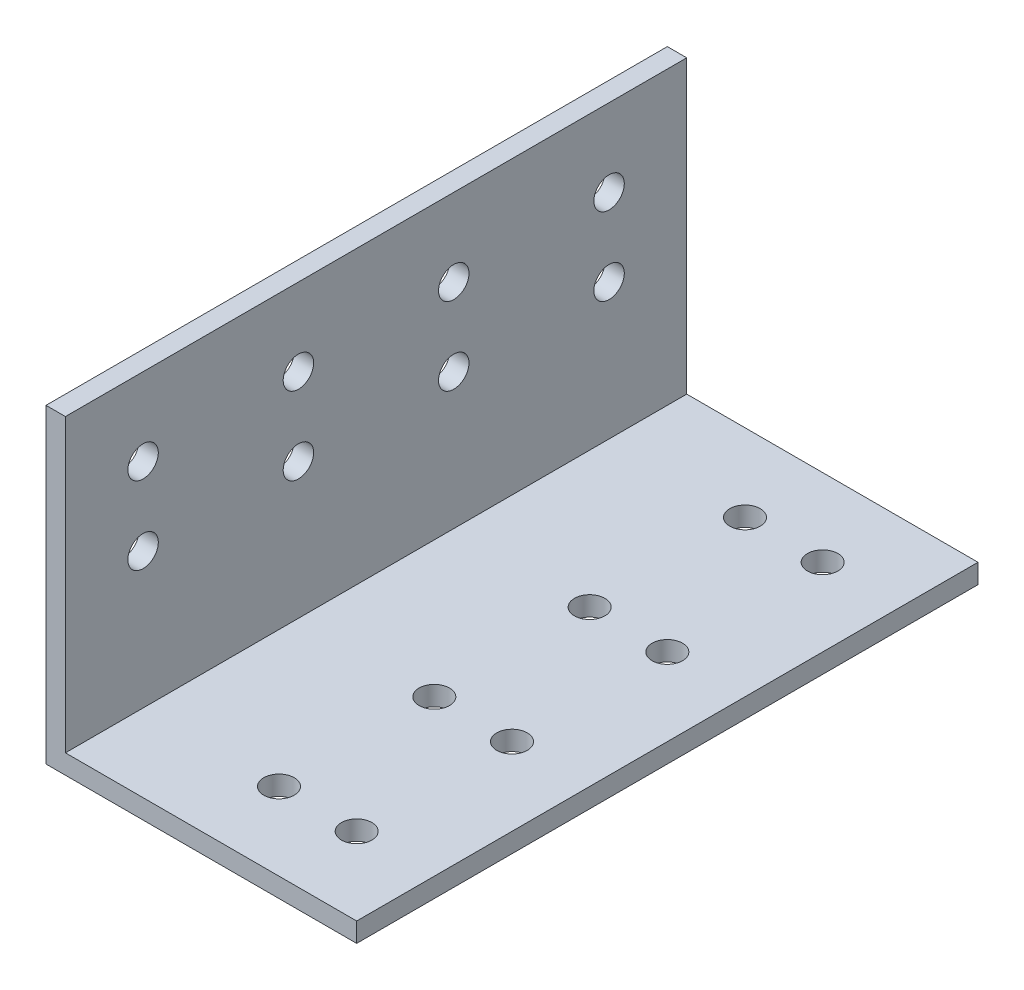
SolidWorks part; units mm, degrees
material "6061-T6 (SS)"
ref_plane "Front Plane" through (0, 0, 0) normal (0, 0, 1) x (1, 0, 0)
ref_plane "Top Plane" through (0, 0, 0) normal (0, 1, 0) x (1, 0, 0)
ref_plane "Right Plane" through (0, 0, 0) normal (1, 0, 0) x (0, 0, -1)
sketch "Sketch2" plane through (0, 0, 0) normal (0, 0, 1) x (1, 0, 0)
  line L0 (0, 0) -> (0, 50.8)
  line L1 (0, 50.8) -> (3.175, 50.8)
  line L2 (3.175, 50.8) -> (3.175, 3.175)
  line L3 (3.175, 3.175) -> (50.8, 3.175)
  line L4 (50.8, 3.175) -> (50.8, 0)
  line L5 (50.8, 0) -> (0, 0)
  dimension "D1" = 3.175
  dimension "D2" = 50.8
  dimension "D3" = 50.8
extrude "Boss-Extrude1" add sketch "Sketch2" along normal blind 101.6 contours L2 L3 L4 L5 L0 L1
sketch "Sketch3" plane through (0, 3.175, 0) normal (0, 1, 0) x (1, 0, 0)
  line L0 (3.175, -101.6) -> (3.175, 0) construction
  line L1 (3.175, 0) -> (50.8, 0) construction
  circle A0 centre (25.4, -12.7) radius 2.4892
  circle A1 centre (38.1, -12.7) radius 2.4892
  circle A2 centre (38.1, -38.1) radius 2.4892
  circle A3 centre (38.1, -63.5) radius 2.4892
  circle A4 centre (38.1, -88.9) radius 2.4892
  circle A5 centre (25.4, -38.1) radius 2.4892
  circle A6 centre (25.4, -63.5) radius 2.4892
  circle A7 centre (25.4, -88.9) radius 2.4892
  point P20 (0, 0)
  dimension "D3" = 12.7
  dimension "D4" = 25.4
  dimension "D5" = 22.225
  dimension "D6" = 4.9784
  dimension "D7" = 12.7
  dimension "D1" = 2
  dimension "D2" = 4
extrude "Cut-Extrude1" cut sketch "Sketch3" against normal through all
sketch "Sketch4" plane through (3.175, 0, 0) normal (1, 0, 0) x (0, 0, -1)
  line L0 (0, 50.8) -> (0, 3.175) construction
  line L1 (-101.6, 3.175) -> (0, 3.175) construction
  circle A0 centre (-12.7, 25.4) radius 2.4892
  circle A1 centre (-38.1, 25.4) radius 2.4892
  circle A2 centre (-63.5, 25.4) radius 2.4892
  circle A3 centre (-88.9, 25.4) radius 2.4892
  circle A4 centre (-38.1, 38.1) radius 2.4892
  circle A5 centre (-63.5, 38.1) radius 2.4892
  circle A6 centre (-88.9, 38.1) radius 2.4892
  circle A7 centre (-12.7, 38.1) radius 2.4892
  point P20 (0, 0)
  point P21 (0, 0)
  dimension "D3" = 12.7
  dimension "D4" = 12.7
  dimension "D5" = 25.4
  dimension "D6" = 22.225
  dimension "D7" = 4.9784
  dimension "D1" = 4
  dimension "D2" = 2
extrude "Cut-Extrude2" cut sketch "Sketch4" against normal through all
